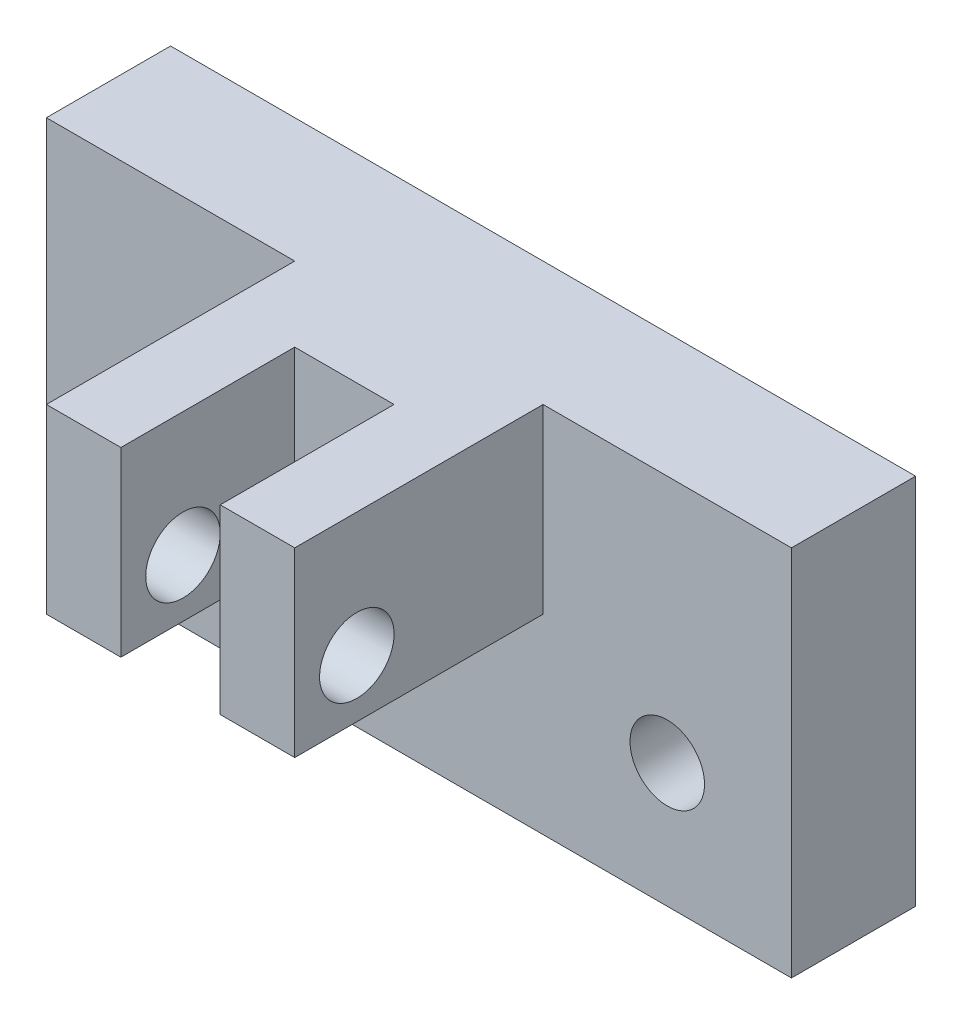
SolidWorks part; units mm, degrees
ref_plane "前视基准面" through (0, 0, 0) normal (0, 0, 1) x (1, 0, 0)
ref_plane "上视基准面" through (0, 0, 0) normal (0, 1, 0) x (1, 0, 0)
ref_plane "右视基准面" through (0, 0, 0) normal (1, 0, 0) x (0, 0, -1)
sketch "草图1" plane through (0, 0, 0) normal (0, 0, 1) x (1, 0, 0)
  line L1 (0, 0) -> (30, 0)
  line L2 (0, 0) -> (0, 15)
  line L3 (0, 15) -> (30, 15)
  line L4 (30, 0) -> (30, 15)
  line L5 (0, 0) -> (30, 15) construction
  line L6 (0, 15) -> (30, 0) construction
  point P4 (15, 7.5)
  dimension "D1" = 15
  dimension "D2" = 30
extrude "凸台-拉伸1" add sketch "草图1" along normal blind 5
sketch "草图2" plane through (0, 0, 5) normal (0, 0, 1) x (1, 0, 0)
  line L0 (30, 15) -> (0, 15) construction
  line L1 (10, 15) -> (20, 15)
  line L2 (10, 15) -> (10, 7.6858)
  line L3 (10, 7.6858) -> (20, 7.6858)
  line L4 (20, 15) -> (20, 7.6858)
  line L5 (10, 15) -> (20, 7.6858) construction
  line L6 (10, 7.6858) -> (20, 15) construction
  line L7 (0, 15) -> (0, 0) construction
  point P4 (15, 11.3429)
  dimension "D1" = 10
  dimension "D2" = 10
extrude "凸台-拉伸2" add sketch "草图2" along normal blind 10
sketch "草图3" plane through (0, 0, 5) normal (0, 0, 1) x (1, 0, 0)
  line L0 (0, 15) -> (0, 0) construction
  line L1 (0, 0) -> (30, 0) construction
  circle A0 centre (5, 5) radius 1.5
  circle A1 centre (25, 5) radius 1.5
  dimension "D1" = 3
  dimension "D2" = 3
  dimension "D3" = 20
  dimension "D4" = 5
  dimension "D5" = 5
extrude "切除-拉伸1" cut sketch "草图3" against normal blind 6.5
sketch "草图4" plane through (0, 0, 15) normal (0, 0, 1) x (1, 0, 0)
  line L0 (20, 15) -> (10, 15) construction
  line L1 (13, 15) -> (17, 15)
  line L2 (13, 15) -> (13, 7.6858)
  line L3 (13, 7.6858) -> (17, 7.6858)
  line L4 (17, 15) -> (17, 7.6858)
  line L5 (13, 15) -> (17, 7.6858) construction
  line L6 (13, 7.6858) -> (17, 15) construction
  line L7 (10, 7.6858) -> (20, 7.6858) construction
  line L8 (10, 15) -> (10, 7.6858) construction
  line L9 (20, 7.6858) -> (20, 15) construction
  point P4 (15, 11.3429)
  dimension "D1" = 3
  dimension "D2" = 3
extrude "切除-拉伸2" cut sketch "草图4" against normal blind 7
sketch "草图5" plane through (10, 0, 0) normal (-1, 0, 0) x (0, 0, 1)
  line L0 (15, 15) -> (15, 7.6858) construction
  line L1 (15, 15) -> (5, 15) construction
  circle A0 centre (12.5, 10) radius 1.5
  dimension "D1" = 3
  dimension "D2" = 2.5
  dimension "D3" = 5
extrude "切除-拉伸3" cut sketch "草图5" against normal blind 15 contours A0
